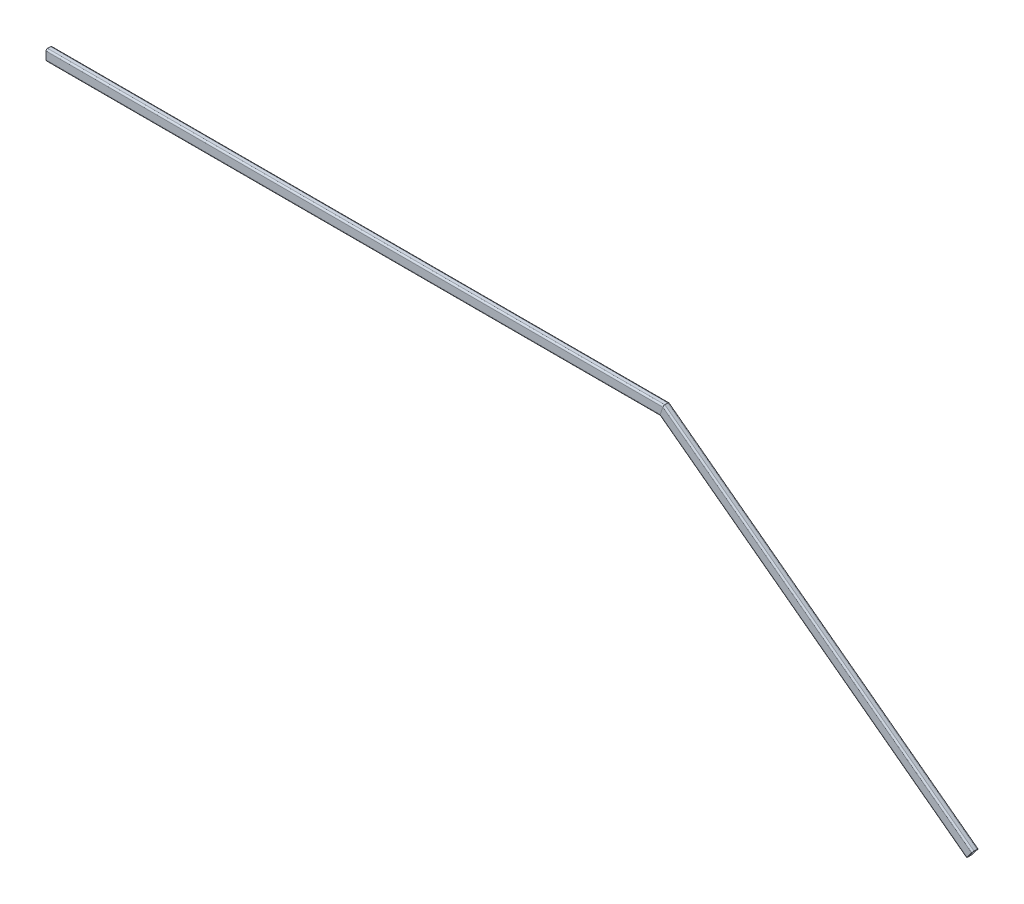
SolidWorks part; units mm, degrees
ref_plane "Front Plane" through (0, 0, 0) normal (0, 0, 1) x (1, 0, 0)
ref_plane "Top Plane" through (0, 0, 0) normal (0, 1, 0) x (1, 0, 0)
ref_plane "Right Plane" through (0, 0, 0) normal (1, 0, 0) x (0, 0, -1)
sketch "Sketch2" plane through (0, 0, 0) normal (0, 0, 1) x (1, 0, 0)
  line L0 (0, 0) -> (4000, 0)
  line L1 (4000, 0) -> (6000, -1500)
  point P3 (1500, 0)
  dimension "D1" = 4000
  dimension "D2" = 2000
  dimension "D3" = 1500
  dimension "D4" = 1500
other "Structural Member1"
ref_plane "Plane1" through (0, 0, 0) normal (1, 0, 0) x (0, 0, 1)
sketch "Sketch1" plane through (0, 0, 0) normal (1, 0, 0) x (0, 0, 1)
  line L0 (-10, -30) -> (10, -30)
  line L1 (-15, -25) -> (-15, 25)
  line L2 (10, 30) -> (-10, 30)
  line L3 (15, 25) -> (15, -25)
  line L4 (-10, -35) -> (10, -35)
  line L5 (-20, -25) -> (-20, 25)
  line L6 (10, 35) -> (-10, 35)
  line L7 (20, 25) -> (20, -25)
  arc A0 (20, 25) -> (10, 35) centre (10, 25) ccw
  arc A1 (10, -35) -> (20, -25) centre (10, -25) ccw
  arc A2 (-20, -25) -> (-10, -35) centre (-10, -25) ccw
  arc A3 (-10, 35) -> (-20, 25) centre (-10, 25) ccw
  arc A4 (-10, 30) -> (-15, 25) centre (-10, 25) ccw
  arc A5 (15, 25) -> (10, 30) centre (10, 25) ccw
  arc A6 (10, -30) -> (15, -25) centre (10, -25) ccw
  arc A7 (-15, -25) -> (-10, -30) centre (-10, -25) ccw
  point P0 (0, 35)
  point P1 (20, 0)
  point P2 (0, -35)
  point P3 (-20, 0)
  point P4 (-20, 35)
  point P5 (20, 35)
  point P6 (20, -35)
  point P7 (-20, -35)
  point P8 (0, 0)
  point P33 (0, 0)
  dimension "D1" = 10
  dimension "Thickness" = 5
  dimension "V_leg" = 70
  dimension "H_leg" = 40
ref_point "Point1"
